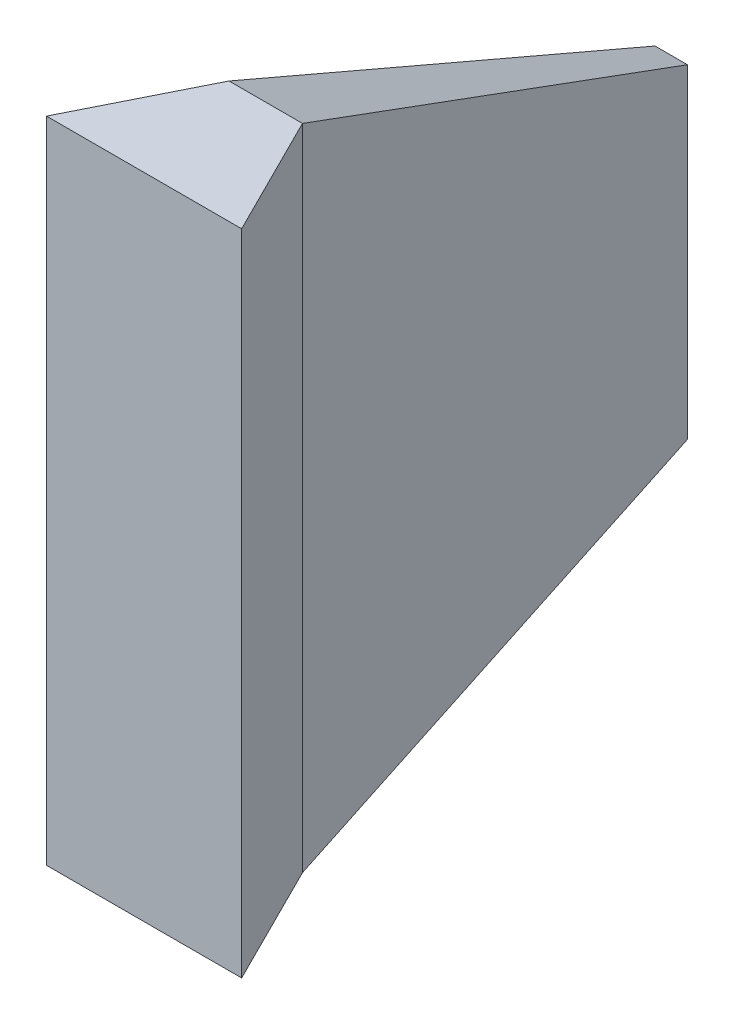
SolidWorks part; units mm, degrees
ref_plane "Front Plane" through (0, 0, 0) normal (0, 0, 1) x (1, 0, 0)
ref_plane "Top Plane" through (0, 0, 0) normal (0, 1, 0) x (1, 0, 0)
ref_plane "Right Plane" through (0, 0, 0) normal (1, 0, 0) x (0, 0, -1)
sketch "Sketch1" plane through (0, 0, 0) normal (0, 1, 0) x (1, 0, 0)
  line L0 (-24.06, 0) -> (-16.56, 14.9994)
  line L1 (-16.56, 14.9994) -> (-7.5, 14.9994)
  line L2 (-7.5, 14.9994) -> (0, 0)
  line L3 (0, 0) -> (-24.06, 0)
  point P2 (-23.4779, 0)
  point P5 (-6.7725, 14.9898)
  dimension "D1" = 16.77
  dimension "D2" = 9.06
  dimension "D3" = 16.77
  dimension "D4" = 24.06
extrude "Boss-Extrude1" add sketch "Sketch1" along normal blind 80
sketch "Sketch2" plane through (0, 0, -14.9994) normal (0, 0, -1) x (-1, 0, 0)
  line L1 (7.5, 80) -> (16.56, 80)
  line L2 (7.5, 80) -> (7.5, 0)
  line L3 (7.5, 0) -> (16.56, 0)
  line L4 (16.56, 80) -> (16.56, 0)
extrude "Boss-Extrude2" add sketch "Sketch2" along normal blind 50
sketch "Sketch3" plane through (-16.56, 0, 0) normal (-1, 0, 0) x (0, 0, 1)
  line L0 (-14.9994, 80) -> (-64.9994, 60)
  line L1 (-64.9994, 0) -> (-64.9994, 80) construction
  line L2 (-64.9994, 60) -> (-64.9994, 80)
  line L3 (-64.9994, 80) -> (-14.9994, 80)
  line L4 (-64.9994, 0) -> (-64.9994, 20)
  line L5 (-64.9994, 20) -> (-14.9994, 0)
  line L6 (-14.9994, 0) -> (-64.9994, 0)
  point P10 (-64.9994, 60.4017)
  dimension "D1" = 40
extrude "Cut-Extrude1" cut sketch "Sketch3" against normal through all
ref_plane "Plane1" through (-7.5, 20, -64.9994) normal (1, 0, 0) x (0, 0, -1)
sketch "Sketch7" plane through (0, 80, 0) normal (0, 1, 0) x (1, 0, 0)
  line L0 (-16.56, 14.9994) -> (-14.03, 64.9994)
  line L1 (-7.5, 64.9994) -> (-16.56, 64.9994) construction
  line L2 (-14.03, 64.9994) -> (-16.56, 64.9994)
  line L3 (-16.56, 64.9994) -> (-16.56, 14.9994)
  line L4 (-7.5, 14.9994) -> (-7.5, 64.9994)
  line L5 (-7.5, 62.5079) -> (-7.5, 67.4909) construction
  line L6 (-7.5, 64.9994) -> (-7.5, 14.9994) construction
  line L7 (-7.5, 64.9994) -> (-10.03, 64.9994)
  line L8 (-10.03, 64.9994) -> (-7.5, 14.9994)
  point P14 (-14.3056, 64.9994)
  dimension "D1" = 4
extrude "Cut-Extrude2" cut sketch "Sketch7" against normal through all
